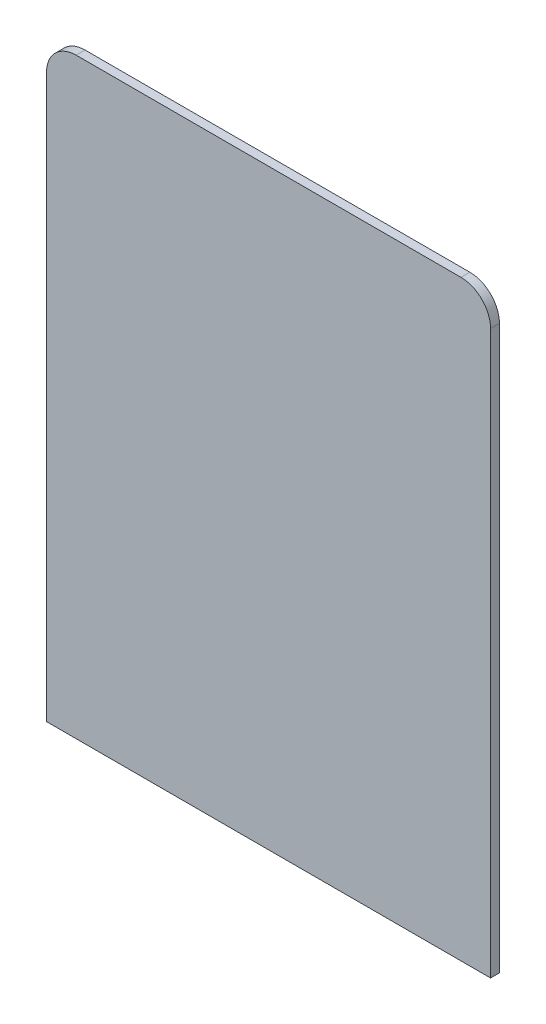
SolidWorks part; units mm, degrees
ref_plane "Спереди" through (0, 0, 0) normal (0, 0, 1) x (1, 0, 0)
ref_plane "Сверху" through (0, 0, 0) normal (0, 1, 0) x (1, 0, 0)
ref_plane "Справа" through (0, 0, 0) normal (1, 0, 0) x (0, 0, -1)
other "Configuration Table"
sketch "Эскиз1" plane through (0, 0, 0) normal (0, 0, 1) x (1, 0, 0)
  line L1 (-65, 100) -> (65, 100)
  line L2 (-75, 90) -> (-75, -100)
  line L3 (-75, -100) -> (75, -100)
  line L4 (75, 90) -> (75, -100)
  line L5 (-75, 100) -> (75, -100) construction
  line L6 (-75, -100) -> (75, 100) construction
  arc A0 (75, 90) -> (65, 100) centre (65, 90) ccw
  arc A1 (-65, 100) -> (-75, 90) centre (-65, 90) ccw
  point P0 (0, 0)
  dimension "D3" = 10
  dimension "D1" = 150
  dimension "D2" = 200
extrude "Бобышка-Вытянуть1" add sketch "Эскиз1" along normal mid plane 3
